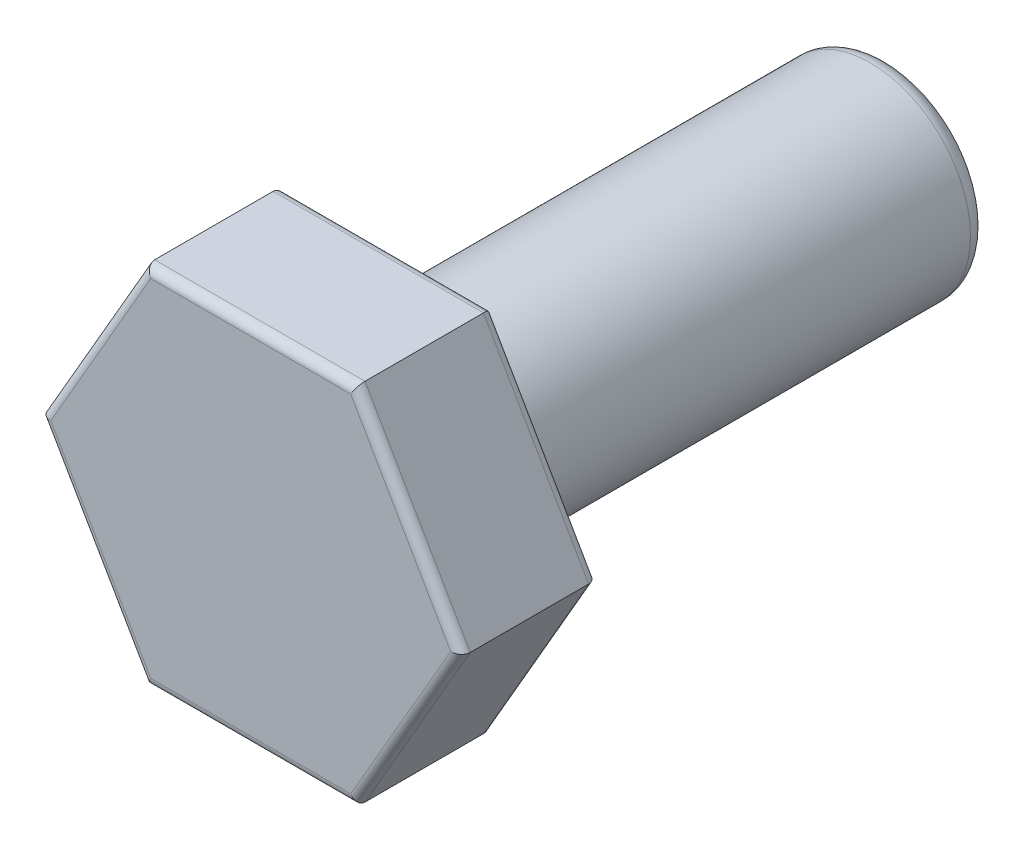
SolidWorks part; units mm, degrees
ref_plane "前视基准面" through (0, 0, 0) normal (0, 0, 1) x (1, 0, 0)
ref_plane "上视基准面" through (0, 0, 0) normal (0, 1, 0) x (1, 0, 0)
ref_plane "右视基准面" through (0, 0, 0) normal (1, 0, 0) x (0, 0, -1)
sketch "草图1" plane through (0, 0, 0) normal (0, 0, 1) x (1, 0, 0)
  circle A0 centre (0, 0) radius 11
  dimension "D1" = 22
extrude "凸台-拉伸1" add sketch "草图1" along normal blind 55
sketch "草图2" plane through (0, 0, 55) normal (0, 0, 1) x (1, 0, 0)
  line L1 (11.547, -20) -> (23.094, 0)
  line L2 (23.094, 0) -> (11.547, 20)
  line L3 (11.547, 20) -> (-11.547, 20)
  line L4 (-11.547, 20) -> (-23.094, 0)
  line L5 (-23.094, 0) -> (-11.547, -20)
  line L6 (-11.547, -20) -> (11.547, -20)
  circle A0 centre (0, 0) radius 20 construction
  dimension "D1" = 40
extrude "凸台-拉伸2" add sketch "草图2" along normal blind 15
fillet "圆角1" radius 1 12 edges at (0, -20, 55) (-17.3205, -10, 70) (-17.3205, -10, 55) (-17.3205, 10, 55) (-17.3205, 10, 70) (0, 20, 70) (0, 20, 55) (17.3205, 10, 55) (17.3205, -10, 70) (17.3205, 10, 70) (17.3205, -10, 55) (0, -20, 70)
fillet "圆角2" radius 2 1 edges at (11, 0, 0)
